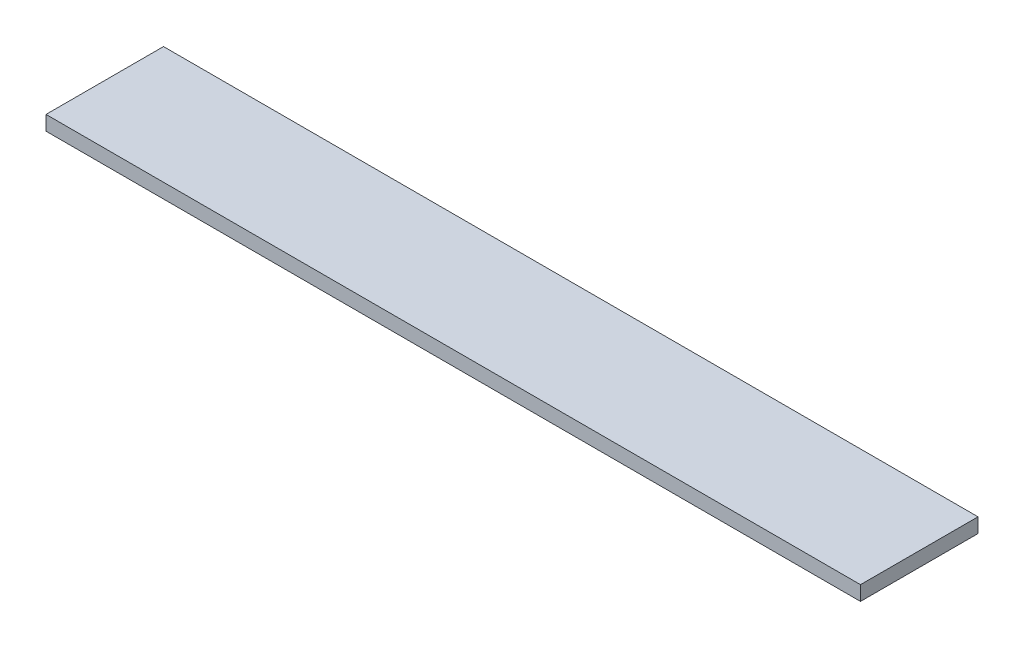
SolidWorks part; units mm, degrees
material "6061 Alloy"
ref_plane "Front Plane" through (0, 0, 0) normal (0, 0, 1) x (1, 0, 0)
ref_plane "Top Plane" through (0, 0, 0) normal (0, 1, 0) x (1, 0, 0)
ref_plane "Right Plane" through (0, 0, 0) normal (1, 0, 0) x (0, 0, -1)
sketch "Sketch1" plane through (0, 0, 0) normal (0, 0, 1) x (1, 0, 0)
  line L1 (0, 0) -> (177.8, 0)
  line L2 (0, 0) -> (0, -3.175)
  line L3 (0, -3.175) -> (177.8, -3.175)
  line L4 (177.8, 0) -> (177.8, -3.175)
  dimension "D1" = 177.8
  dimension "D2" = 3.175
extrude "Boss-Extrude1" add sketch "Sketch1" along normal blind 25.654
